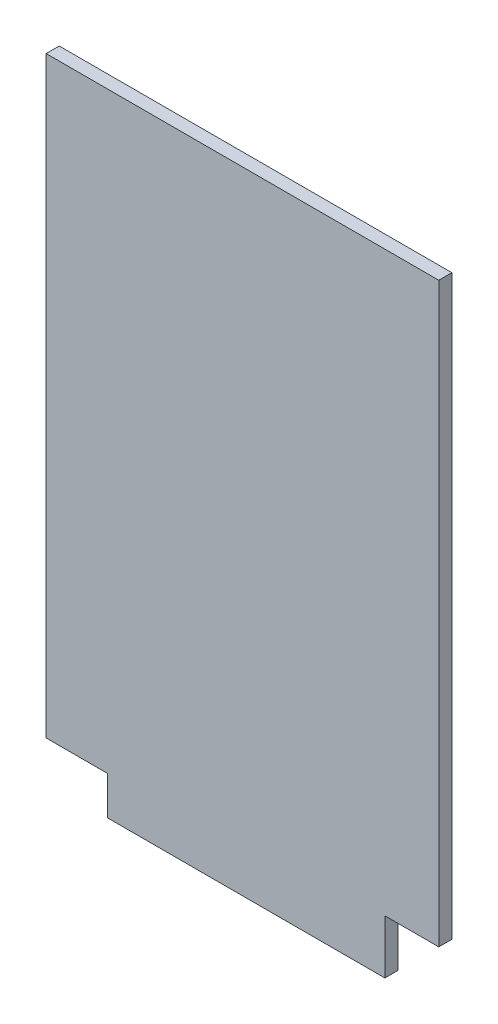
SolidWorks part; units mm, degrees
ref_plane "Front Plane" through (0, 0, 0) normal (0, 0, 1) x (1, 0, 0)
ref_plane "Top Plane" through (0, 0, 0) normal (0, 1, 0) x (1, 0, 0)
ref_plane "Right Plane" through (0, 0, 0) normal (1, 0, 0) x (0, 0, -1)
sketch "Sketch1" plane through (0, 0, 0) normal (0, 0, 1) x (1, 0, 0)
  line L0 (8, 0) -> (8, 5)
  line L1 (44, 0) -> (8, 0)
  line L2 (0, 5) -> (0, 82)
  line L3 (0, 82) -> (51, 82)
  line L4 (51, 7) -> (51, 82)
  line L5 (8, 5) -> (0, 5)
  line L8 (51, 7) -> (44, 7)
  line L9 (44, 7) -> (44, 0)
  point P3 (7.8854, 0)
  dimension "D1" = 51
  dimension "D2" = 7
  dimension "D3" = 8
  dimension "D4" = 7
  dimension "D5" = 5
  dimension "D6" = 8
  dimension "D7" = 75
extrude "Boss-Extrude1" add sketch "Sketch1" along normal blind 1.7
